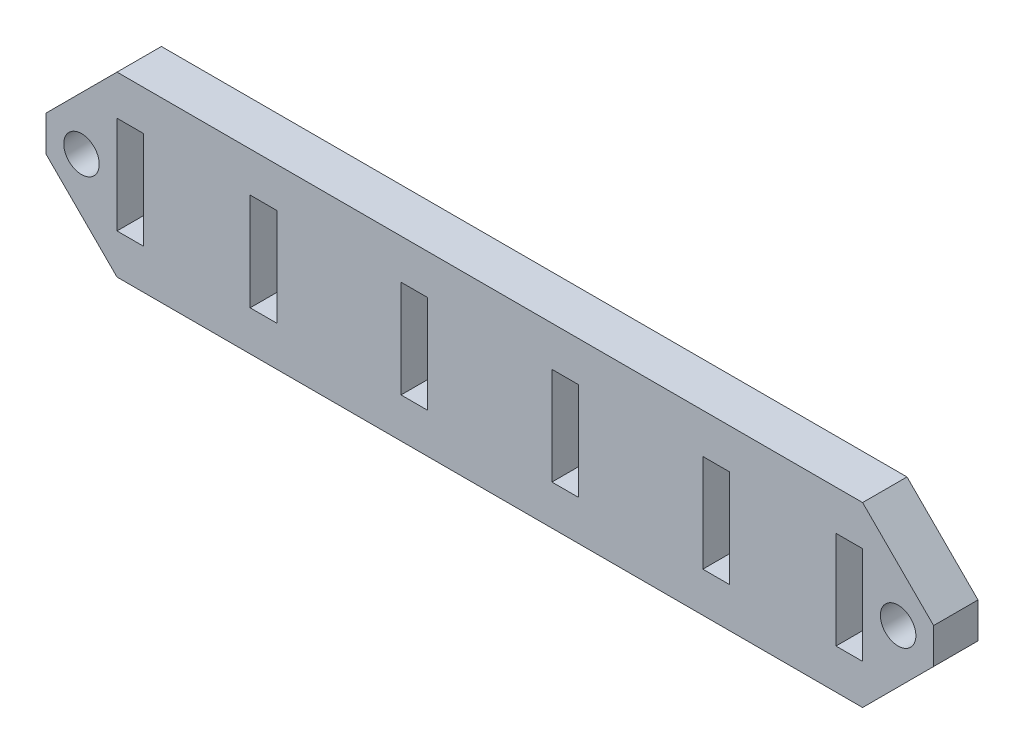
SolidWorks part; units mm, degrees
ref_plane "Front Plane" through (0, 0, 0) normal (0, 0, 1) x (1, 0, 0)
ref_plane "Top Plane" through (0, 0, 0) normal (0, 1, 0) x (1, 0, 0)
ref_plane "Right Plane" through (0, 0, 0) normal (1, 0, 0) x (0, 0, -1)
sketch "Sketch1" plane through (0, 0, 0) normal (0, 0, 1) x (1, 0, 0)
  line L1 (100, 20) -> (0, 20)
  line L2 (100, 20) -> (100, 0)
  line L3 (100, 0) -> (0, 0)
  line L4 (0, 20) -> (0, 0)
  dimension "D1" = 20
  dimension "D2" = 100
extrude "Boss-Extrude1" add sketch "Sketch1" along normal blind 5 contours L3 L4 L1 L2
sketch "Sketch2" plane through (0, 0, 0) normal (0, 0, -1) x (-1, 0, 0)
  line L0 (-100, 20) -> (-100, 0) construction
  line L1 (-92, 15.5) -> (-89, 15.5)
  line L2 (-92, 15.5) -> (-92, 4.5)
  line L3 (-92, 4.5) -> (-89, 4.5)
  line L4 (-89, 15.5) -> (-89, 4.5)
  line L5 (-77, 4.5) -> (-74, 4.5)
  line L6 (-77, 4.5) -> (-77, 15.5)
  line L7 (-77, 15.5) -> (-74, 15.5)
  line L8 (-74, 4.5) -> (-74, 15.5)
  line L9 (-60, 15.5) -> (-57, 15.5)
  line L10 (-60, 15.5) -> (-60, 4.5)
  line L11 (-60, 4.5) -> (-57, 4.5)
  line L12 (-57, 15.5) -> (-57, 4.5)
  line L13 (-43, 15.5) -> (-40, 15.5)
  line L14 (-43, 15.5) -> (-43, 4.5)
  line L15 (-43, 4.5) -> (-40, 4.5)
  line L16 (-40, 15.5) -> (-40, 4.5)
  line L17 (-26, 15.5) -> (-23, 15.5)
  line L18 (-26, 15.5) -> (-26, 4.5)
  line L19 (-26, 4.5) -> (-23, 4.5)
  line L20 (-23, 15.5) -> (-23, 4.5)
  line L21 (-11, 15.5) -> (-8, 15.5)
  line L22 (-11, 15.5) -> (-11, 4.5)
  line L23 (-11, 4.5) -> (-8, 4.5)
  line L24 (-8, 15.5) -> (-8, 4.5)
  line L25 (0, 20) -> (0, 0) construction
  line L26 (-100, 20) -> (0, 20) construction
  line L27 (-100, 0) -> (0, 0) construction
  circle A0 centre (-96, 10) radius 2
  circle A1 centre (-4, 10) radius 2
  dimension "D7" = 4
  dimension "D8" = 4
  dimension "D20" = 4
  dimension "D30" = 10
  dimension "D1" = 11
  dimension "D2" = 11
  dimension "D3" = 11
  dimension "D4" = 11
  dimension "D5" = 11
  dimension "D6" = 11
  dimension "D9" = 8
  dimension "D10" = 3
  dimension "D11" = 12
  dimension "D12" = 14
  dimension "D13" = 3
  dimension "D14" = 3
  dimension "D15" = 14
  dimension "D16" = 3
  dimension "D17" = 14
  dimension "D18" = 3
  dimension "D19" = 4.5
  dimension "D21" = 10
  dimension "D22" = 8
  dimension "D23" = 4.5
  dimension "D24" = 4.5
  dimension "D25" = 4.5
  dimension "D26" = 4.5
  dimension "D27" = 4.5
  dimension "D28" = 11
  dimension "D29" = 10
  dimension "D31" = 4
  dimension "D32" = 3
extrude "Cut-Extrude1" cut sketch "Sketch2" against normal blind 5
sketch "Sketch3" plane through (0, 0, 0) normal (0, 0, -1) x (-1, 0, 0)
  line L0 (-92, 20) -> (-100, 12)
  line L1 (-100, 20) -> (0, 20) construction
  line L2 (-100, 20) -> (-100, 0) construction
  line L3 (-100, 12) -> (-100, 20)
  line L4 (-100, 20) -> (-92, 20)
  line L5 (-100, 8) -> (-100, 0)
  line L6 (-100, 0) -> (-92, 0)
  line L7 (-100, 0) -> (0, 0) construction
  line L8 (-92, 0) -> (-100, 8)
  line L9 (-8, 20) -> (0, 20)
  line L10 (0, 20) -> (0, 12)
  line L11 (0, 20) -> (0, 0) construction
  line L12 (0, 12) -> (-8, 20)
  line L13 (0, 8) -> (-8, 0)
  line L14 (-8, 0) -> (0, 0)
  line L15 (0, 0) -> (0, 8)
  dimension "D1" = 8
  dimension "D2" = 8
  dimension "D3" = 8
  dimension "D4" = 8
  dimension "D5" = 8
  dimension "D6" = 8
  dimension "D7" = 8
  dimension "D8" = 8
extrude "Cut-Extrude2" cut sketch "Sketch3" against normal blind 5
